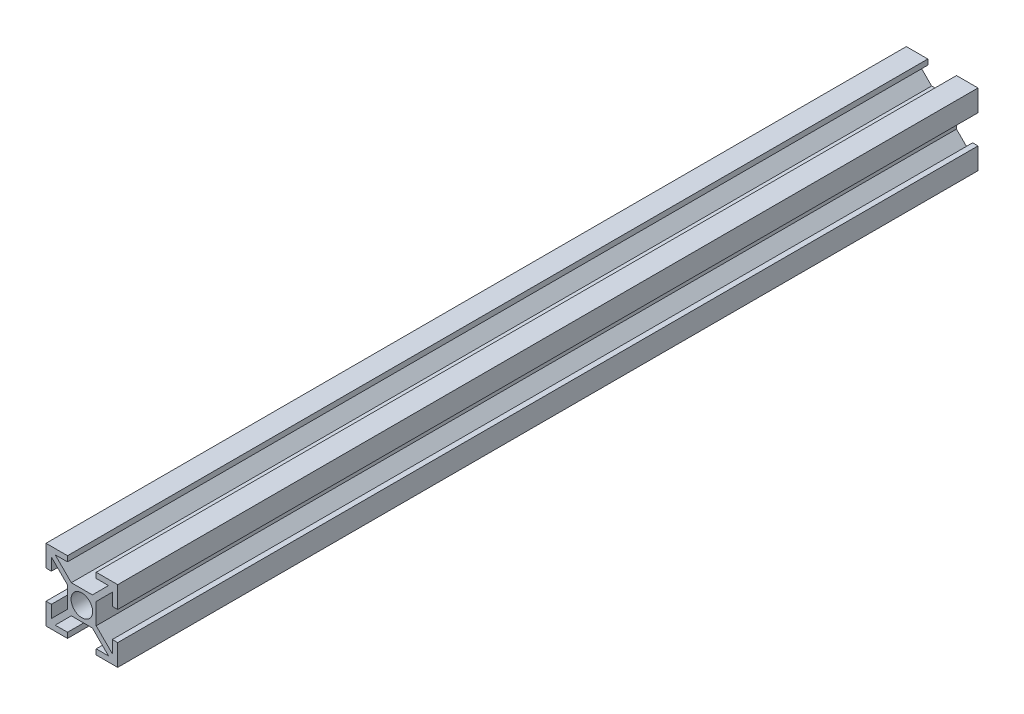
SolidWorks part; units mm, degrees
ref_plane "Plano frontal" through (0, 0, 0) normal (0, 0, 1) x (1, 0, 0)
ref_plane "Plano superior" through (0, 0, 0) normal (0, 1, 0) x (1, 0, 0)
ref_plane "Plano direito" through (0, 0, 0) normal (1, 0, 0) x (0, 0, -1)
sketch "Esboço1" plane through (0, 0, 0) normal (0, 0, 1) x (1, 0, 0)
  line L0 (-2.9393, 4) -> (2.9393, 4)
  line L1 (-10, -10) -> (-4, -10)
  line L2 (-10, -10) -> (-10, -4)
  line L3 (-10, 10) -> (-4, 10)
  line L4 (10, -10) -> (10, -4)
  line L5 (-10, -10) -> (-4, -4) construction
  line L6 (-10, 10) -> (0, 0) construction
  line L7 (-7.4393, -8.5) -> (-2.9393, -4)
  line L8 (4, -10) -> (10, -10)
  line L9 (-8.5, -7.4393) -> (-4, -2.9393)
  line L10 (-8.5, 7.4393) -> (-4, 2.9393)
  line L11 (-7.4393, -8.5) -> (-4, -8.5)
  line L12 (-8.5, -7.4393) -> (-8.5, -4)
  line L13 (-7.4393, 8.5) -> (-4, 8.5)
  line L14 (8.5, -7.4393) -> (8.5, -4)
  line L17 (-4, 10) -> (-4, 8.5)
  line L18 (4, -8.5) -> (7.4393, -8.5)
  line L19 (-10, -4) -> (-8.5, -4)
  line L20 (4, 10) -> (4, 8.5)
  line L21 (-10, 4) -> (-8.5, 4)
  line L22 (-4, 2.9393) -> (-4, -2.9393)
  line L23 (-4, -8.5) -> (-4, -10)
  line L24 (-8.5, 4) -> (-8.5, 7.4393)
  line L25 (-10, 4) -> (-10, 10)
  line L26 (-7.4393, 8.5) -> (-2.9393, 4)
  line L27 (4, 8.5) -> (7.4393, 8.5)
  line L28 (-2.9393, -4) -> (2.9393, -4)
  line L29 (4, 10) -> (10, 10)
  line L30 (4, -8.5) -> (4, -10)
  line L31 (10, 4) -> (10, 10)
  line L32 (8.5, 4) -> (8.5, 7.4393)
  line L33 (-10.5303, -9.4697) -> (9.4697, 10.5303) construction
  line L34 (8.5, 4) -> (10, 4)
  line L35 (8.5, -4) -> (10, -4)
  line L36 (-10, -10) -> (10, 10) construction
  line L37 (4, 2.9393) -> (4, -2.9393)
  line L38 (-9.4697, -10.5303) -> (10.5303, 9.4697) construction
  line L40 (2.9393, -4) -> (7.4393, -8.5)
  line L41 (4, -4) -> (10, -10) construction
  line L43 (4, -2.9393) -> (8.5, -7.4393)
  line L44 (4, 0) -> (10, 0) construction
  line L45 (4, 2.9393) -> (8.5, 7.4393)
  line L47 (4, 4) -> (10, 10) construction
  line L48 (2.9393, 4) -> (7.4393, 8.5)
  circle A0 centre (0, 0) radius 3
  point P0 (0, 0)
  point P14 (-4.0323, -3.9672)
  dimension "D5" = 6
  dimension "D1" = 0.75
  dimension "D3" = 1.5
  dimension "D4" = 20
  dimension "D6" = 8
  dimension "D7" = 20
  dimension "D9" = 1.5
  dimension "D2" = 8
extrude "Ressalto-extrusão1" add sketch "Esboço1" along normal blind 240
